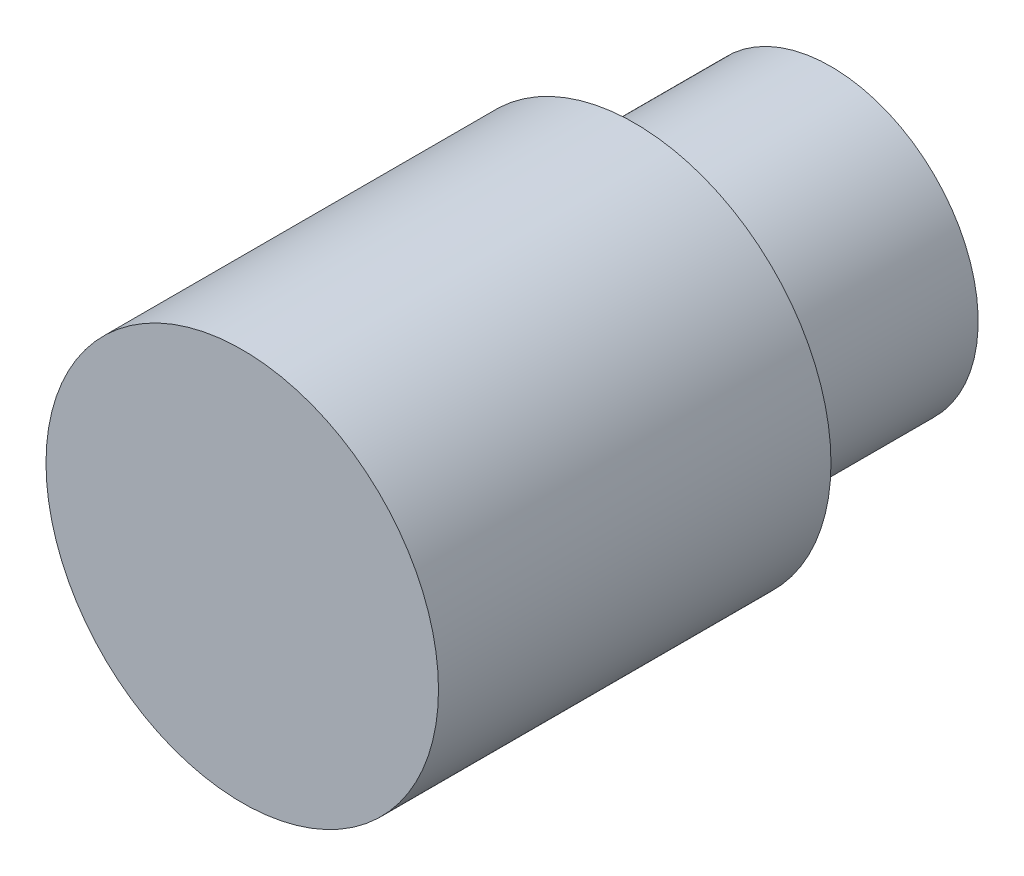
SolidWorks part; units mm, degrees
ref_plane "Front Plane" through (0, 0, 0) normal (0, 0, 1) x (1, 0, 0)
ref_plane "Top Plane" through (0, 0, 0) normal (0, 1, 0) x (1, 0, 0)
ref_plane "Right Plane" through (0, 0, 0) normal (1, 0, 0) x (0, 0, -1)
sketch "Sketch2" plane through (0, 0, 0) normal (1, 0, 0) x (0, 0, -1)
  line L0 (0, 0) -> (100, 0)
  line L4 (100, -50) -> (0, -50)
  line L5 (0, -50) -> (0, 0)
  line L6 (100, -50) -> (100, 0)
  dimension "D1" = 100
  dimension "D2" = 50
revolve "Revolve1" add sketch "Sketch2" angle 360 about L0
sketch "Sketch5" plane through (0, 0, -100) normal (0, 0, -1) x (-1, 0, 0)
  circle A0 centre (0, 0) radius 37.5
  dimension "D1" = 75
extrude "Boss-Extrude1" add sketch "Sketch5" along normal blind 50 contours A0
